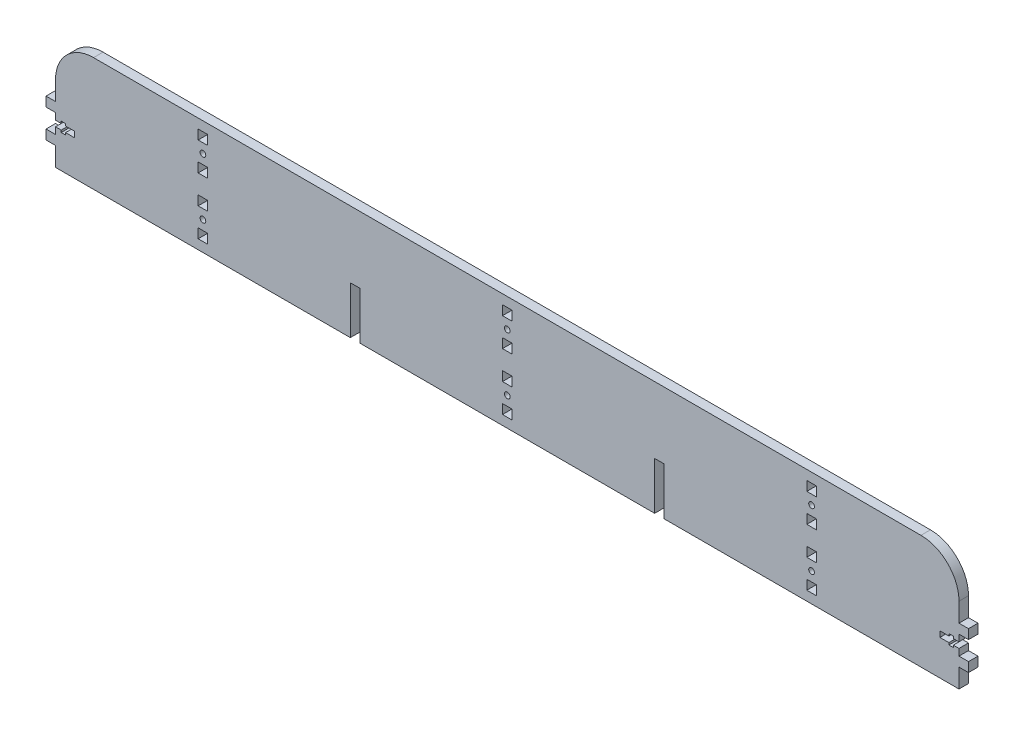
SolidWorks part; units mm, degrees
ref_plane "Plan de face" through (0, 0, 0) normal (0, 0, 1) x (1, 0, 0)
ref_plane "Plan de dessus" through (0, 0, 0) normal (0, 1, 0) x (1, 0, 0)
ref_plane "Plan de droite" through (0, 0, 0) normal (1, 0, 0) x (0, 0, -1)
sketch "Esquisse1" plane through (0, 0, 0) normal (0, 0, 1) x (1, 0, 0)
  line L0 (0, 0) -> (0, 60) construction
  line L1 (0, 60) -> (475, 60) construction
  line L2 (475, 60) -> (475, 0) construction
  line L3 (475, 0) -> (0, 0) construction
  line L4 (157.5, 0) -> (157.5, 60) construction
  line L5 (317.5, 60) -> (317.5, 0) construction
  line L6 (237.5, 0) -> (237.5, 60) construction
  line L7 (0, 20) -> (33.7208, 20) construction
  line L8 (0, 21.5) -> (0, 25)
  line L9 (-5, 25) -> (-5, 30)
  line L10 (-5, 30) -> (0, 30)
  line L11 (-5, 25) -> (0, 25)
  line L12 (0, 18.5) -> (0, 15)
  line L13 (0, 15) -> (-5, 15)
  line L14 (-5, 15) -> (-5, 10)
  line L15 (-5, 10) -> (0, 10)
  line L16 (0, 21.5) -> (0, 18.5) construction
  line L17 (0, 18.5) -> (3, 18.5)
  line L18 (5.3, 18.5) -> (5.3, 17.4)
  line L19 (3, 22.6) -> (5.3, 22.6)
  line L20 (3, 17.4) -> (3, 18.5)
  line L21 (5.3, 18.5) -> (10, 18.5)
  line L22 (10, 18.5) -> (10, 21.5)
  line L23 (10, 21.5) -> (5.3, 21.5)
  line L24 (3, 21.5) -> (3, 22.6)
  line L25 (5.3, 17.4) -> (3, 17.4)
  line L26 (5.3, 22.6) -> (5.3, 21.5)
  line L27 (3, 21.5) -> (0, 21.5)
  line L28 (10, 20) -> (0, 20) construction
  line L29 (480, 30) -> (475, 30)
  line L30 (480, 25) -> (480, 30)
  line L31 (480, 25) -> (475, 25)
  line L32 (475, 21.5) -> (475, 25)
  line L33 (472, 21.5) -> (475, 21.5)
  line L34 (472, 21.5) -> (472, 22.6)
  line L35 (472, 22.6) -> (469.7, 22.6)
  line L36 (469.7, 22.6) -> (469.7, 21.5)
  line L37 (465, 21.5) -> (469.7, 21.5)
  line L38 (465, 18.5) -> (465, 21.5)
  line L39 (469.7, 18.5) -> (465, 18.5)
  line L40 (469.7, 18.5) -> (469.7, 17.4)
  line L41 (469.7, 17.4) -> (472, 17.4)
  line L42 (472, 17.4) -> (472, 18.5)
  line L43 (475, 18.5) -> (472, 18.5)
  line L44 (475, 18.5) -> (475, 15)
  line L45 (475, 15) -> (480, 15)
  line L46 (480, 15) -> (480, 10)
  line L47 (480, 10) -> (475, 10)
  line L48 (0, 0) -> (0, 10)
  line L49 (0, 30) -> (0, 60)
  line L50 (475, 0) -> (475, 10)
  line L51 (475, 30) -> (475, 60)
  line L55 (320, 25) -> (315, 25)
  line L59 (155, 25) -> (160, 25)
  line L62 (475, 0) -> (320, 0)
  line L63 (320, 0) -> (320, 25)
  line L64 (315, 25) -> (315, 0)
  line L65 (315, 0) -> (160, 0)
  line L66 (160, 0) -> (160, 25)
  line L67 (155, 25) -> (155, 0)
  line L68 (155, 0) -> (0, 0)
  line L69 (0, 60) -> (475, 60)
  line L70 (77.5, 60) -> (77.5, 0) construction
  line L71 (397.5, 0) -> (397.5, 60) construction
  line B0 (397.5, 10) -> (397.5, 20) construction
  line B1 (395, 10) -> (395, 5)
  line B2 (395, 10) -> (400, 10)
  line B3 (400, 10) -> (400, 5)
  line B4 (395, 5) -> (400, 5)
  line B5 (395, 20) -> (395, 25)
  line B6 (395, 20) -> (400, 20)
  line B7 (400, 20) -> (400, 25)
  line B8 (395, 25) -> (400, 25)
  line B9 (397.5, 15) -> (390.5276, 15) construction
  circle B10 centre (397.5, 15) radius 1.5
  line B11 (397.5, 40) -> (397.5, 50) construction
  line B12 (395, 40) -> (395, 35)
  line B13 (395, 40) -> (400, 40)
  line B14 (400, 40) -> (400, 35)
  line B15 (395, 35) -> (400, 35)
  line B16 (395, 50) -> (395, 55)
  line B17 (395, 50) -> (400, 50)
  line B18 (400, 50) -> (400, 55)
  line B19 (395, 55) -> (400, 55)
  line B20 (397.5, 45) -> (390.5276, 45) construction
  circle B21 centre (397.5, 45) radius 1.5
  line B22 (237.5, 10) -> (237.5, 20) construction
  line B23 (235, 10) -> (235, 5)
  line B24 (235, 10) -> (240, 10)
  line B25 (240, 10) -> (240, 5)
  line B26 (235, 5) -> (240, 5)
  line B27 (235, 20) -> (235, 25)
  line B28 (235, 20) -> (240, 20)
  line B29 (240, 20) -> (240, 25)
  line B30 (235, 25) -> (240, 25)
  line B31 (237.5, 15) -> (230.5276, 15) construction
  circle B32 centre (237.5, 15) radius 1.5
  line B33 (237.5, 40) -> (237.5, 50) construction
  line B34 (235, 40) -> (235, 35)
  line B35 (235, 40) -> (240, 40)
  line B36 (240, 40) -> (240, 35)
  line B37 (235, 35) -> (240, 35)
  line B38 (235, 50) -> (235, 55)
  line B39 (235, 50) -> (240, 50)
  line B40 (240, 50) -> (240, 55)
  line B41 (235, 55) -> (240, 55)
  line B42 (237.5, 45) -> (230.5276, 45) construction
  circle B43 centre (237.5, 45) radius 1.5
  line B44 (77.5, 10) -> (77.5, 20) construction
  line B45 (75, 10) -> (75, 5)
  line B46 (75, 10) -> (80, 10)
  line B47 (80, 10) -> (80, 5)
  line B48 (75, 5) -> (80, 5)
  line B49 (75, 20) -> (75, 25)
  line B50 (75, 20) -> (80, 20)
  line B51 (80, 20) -> (80, 25)
  line B52 (75, 25) -> (80, 25)
  line B53 (77.5, 15) -> (70.5276, 15) construction
  circle B54 centre (77.5, 15) radius 1.5
  line B55 (77.5, 40) -> (77.5, 50) construction
  line B56 (75, 40) -> (75, 35)
  line B57 (75, 40) -> (80, 40)
  line B58 (80, 40) -> (80, 35)
  line B59 (75, 35) -> (80, 35)
  line B60 (75, 50) -> (75, 55)
  line B61 (75, 50) -> (80, 50)
  line B62 (80, 50) -> (80, 55)
  line B63 (75, 55) -> (80, 55)
  line B64 (77.5, 45) -> (70.5276, 45) construction
  circle B65 centre (77.5, 45) radius 1.5
  dimension "D1" = 157.5
  dimension "D2" = 5
  dimension "D3" = 20
  dimension "D4" = 10
  dimension "D5" = 5
  dimension "D6" = 5
  dimension "D7" = 5.2
  dimension "D8" = 3
  dimension "D9" = 2.3
  dimension "D10" = 3
  dimension "D11" = 10
  dimension "D12" = 475
  dimension "D13" = 160
  dimension "D14" = 30
  dimension "D15" = 60
  dimension "D16" = 5
sketch_block_instance "Trou M3 plots 5mm-1"
sketch_block "Trou M3 plots 5mm" parameters "D2"=3, "D1"=5, "D3"=5, "D4"=10
sketch_block_instance "Trou M3 plots 5mm-3"
sketch_block_instance "Trou M3 plots 5mm-4"
sketch_block_instance "Trou M3 plots 5mm-5"
sketch_block_instance "Trou M3 plots 5mm-6"
sketch_block_instance "Trou M3 plots 5mm-7"
extrude "Boss.-Extru.1" add sketch "Esquisse1" along normal blind 5
fillet "Congé1" radius 20 2 edges at (475, 60, 2.5) (0, 60, 2.5)
